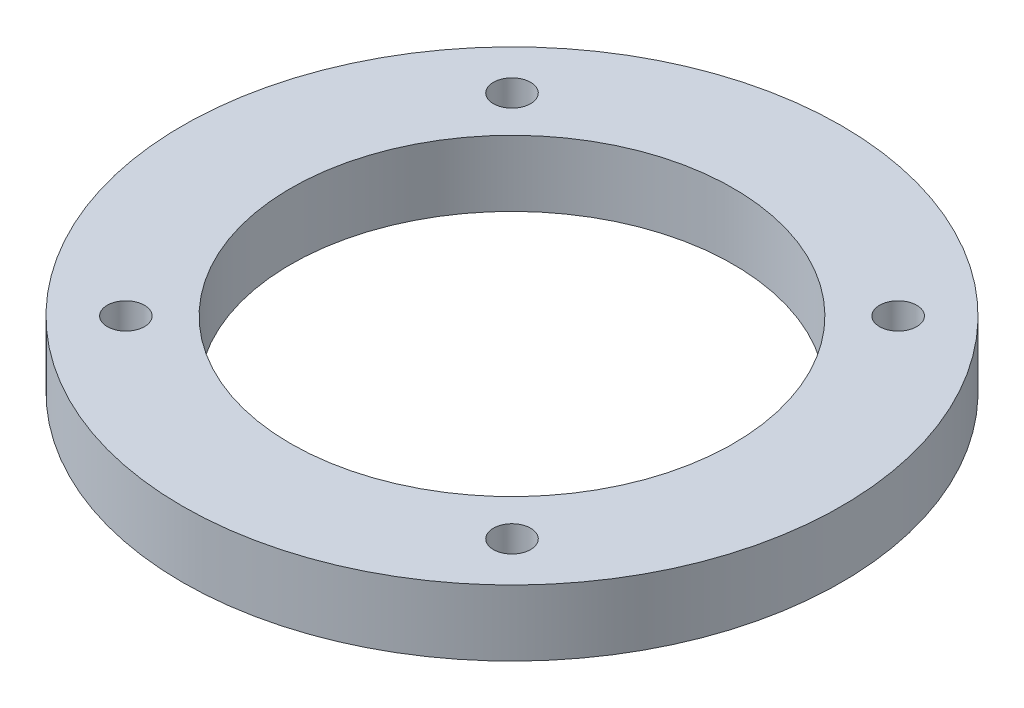
SolidWorks part; units mm, degrees
ref_plane "Front Plane" through (0, 0, 0) normal (0, 0, 1) x (1, 0, 0)
ref_plane "Top Plane" through (0, 0, 0) normal (0, 1, 0) x (1, 0, 0)
ref_plane "Right Plane" through (0, 0, 0) normal (1, 0, 0) x (0, 0, -1)
sketch "Sketch2" plane through (0, 0, 0) normal (0, 1, 0) x (1, 0, 0)
  line L0 (-35, 0) -> (35, 0) construction
  line L1 (0, 35) -> (0, -35) construction
  line L2 (23.5, 25.9374) -> (23.5, -25.9374) construction
  line L3 (-23.5, 25.9374) -> (-23.5, -25.9374) construction
  line L4 (25.9374, 23.5) -> (-25.9374, 23.5) construction
  line L5 (25.9374, -23.5) -> (-25.9374, -23.5) construction
  circle A0 centre (0, 0) radius 35
  circle A1 centre (0, 0) radius 23.5
  circle A2 centre (20.505, 20.505) radius 1.975
  circle A3 centre (-20.505, 20.505) radius 1.975
  circle A4 centre (20.505, -20.505) radius 1.975
  circle A5 centre (-20.505, -20.505) radius 1.975
  dimension "D1" = 70
  dimension "D2" = 47
  dimension "D3" = 3.95
  dimension "D4" = 41.01
  dimension "D5" = 41.01
extrude "Boss-Extrude1" add sketch "Sketch2" along normal blind 7
